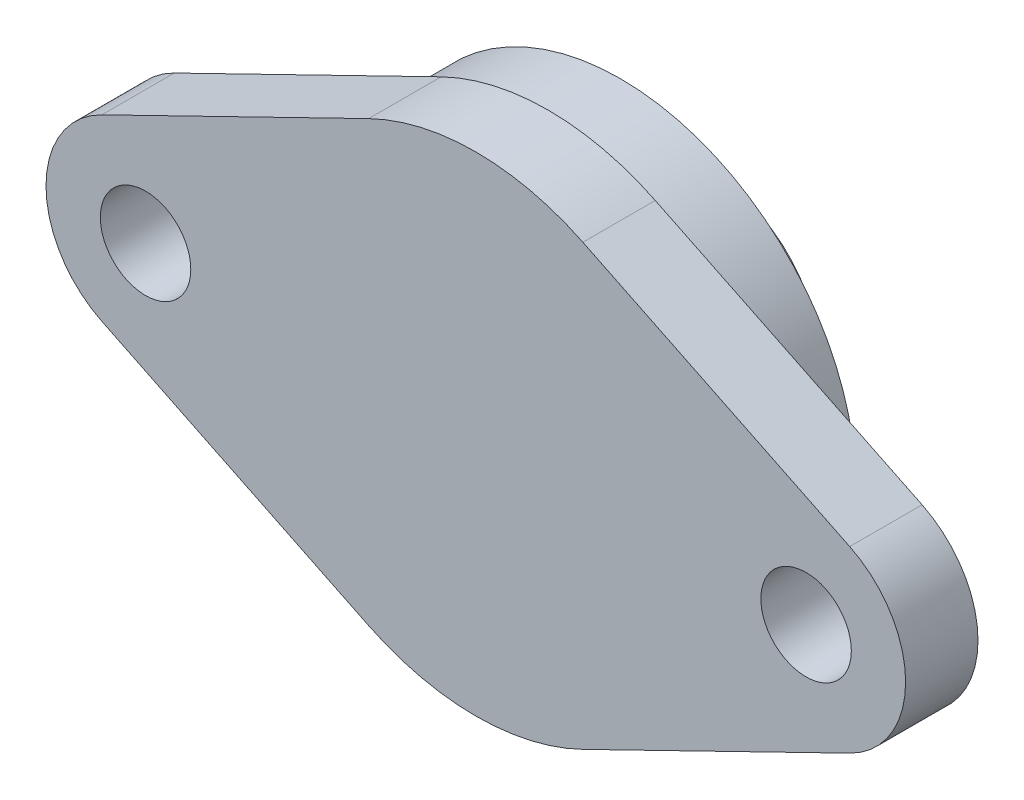
SolidWorks part; units mm, degrees
ref_plane "Front Plane" through (0, 0, 0) normal (0, 0, 1) x (1, 0, 0)
ref_plane "Top Plane" through (0, 0, 0) normal (0, 1, 0) x (1, 0, 0)
ref_plane "Right Plane" through (0, 0, 0) normal (1, 0, 0) x (0, 0, -1)
sketch "Sketch1" plane through (0, 0, 0) normal (0, 0, 1) x (1, 0, 0)
  line L0 (0, 0) -> (0, -13.5) construction
  line L1 (-20.661, 4.9434) -> (-5.9178, 12.1338)
  line L2 (5.9178, 12.1338) -> (20.661, 4.9434)
  line L3 (20.661, -4.9434) -> (5.9178, -12.1338)
  line L4 (-5.9178, -12.1338) -> (-20.661, -4.9434)
  line L5 (-18.25, 0) -> (18.25, 0) construction
  arc A0 (5.9178, 12.1338) -> (-5.9178, 12.1338) centre (0, 0) ccw
  arc A1 (20.661, -4.9434) -> (20.661, 4.9434) centre (18.25, 0) ccw
  arc A2 (-20.661, 4.9434) -> (-20.661, -4.9434) centre (-18.25, 0) ccw
  arc A3 (-5.9178, -12.1338) -> (5.9178, -12.1338) centre (0, 0) ccw
  circle A4 centre (-18.25, 0) radius 2.5
  circle A5 centre (18.25, 0) radius 2.5
  dimension "D1" = 27
  dimension "D2" = 11
  dimension "D4" = 5
  dimension "D3" = 36.5
extrude "Boss-Extrude1" add sketch "Sketch1" along normal blind 4 contours A4 | A5 | L4 A2 L1 A0 L2 A1 L3 A3
sketch "Sketch2" plane through (0, 0, 0) normal (0, 0, -1) x (-1, 0, 0)
  circle A0 centre (0, 0) radius 13
  dimension "D1" = 26
extrude "Extrude-Thin1" add sketch "Sketch2" along normal blind 4 thin thin type one direction reverse wall 2
sketch "Sketch3" plane through (0, 0, 0) normal (0, 0, -1) x (-1, 0, 0)
  circle A0 centre (0, 0) radius 4
  dimension "D1" = 8
extrude "Extrude-Thin2" add sketch "Sketch3" along normal blind 9 thin
sketch "Sketch4" plane through (0, 0, 0) normal (1, 0, 0) x (0, 0, -1)
  circle A0 centre (7, 0) radius 0.75
  point P2 (0, 0)
  dimension "D1" = 1.5
  dimension "D2" = 7
extrude "Cut-Extrude1" cut sketch "Sketch4" against normal through all and the other way through all
sketch "Sketch5" plane through (0, 0, 0) normal (0, 1, 0) x (1, 0, 0)
  circle A0 centre (0, 7) radius 0.75
  point P2 (0, 0)
  dimension "D1" = 1.5
  dimension "D2" = 7
extrude "Cut-Extrude2" cut sketch "Sketch5" against normal through all and the other way through all
